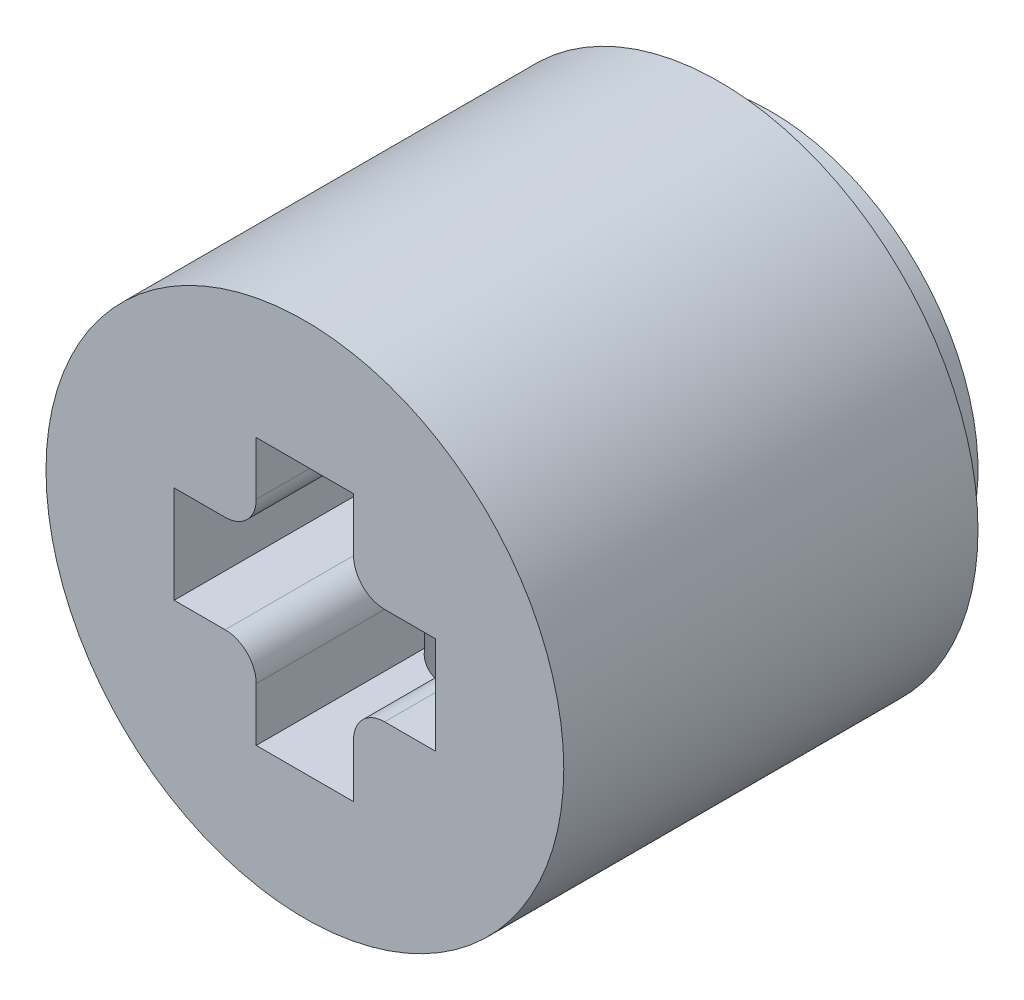
SolidWorks part; units mm, degrees
ref_plane "正面" through (0, 0, 0) normal (0, 0, 1) x (1, 0, 0)
ref_plane "平面" through (0, 0, 0) normal (0, 1, 0) x (1, 0, 0)
ref_plane "右側面" through (0, 0, 0) normal (1, 0, 0) x (0, 0, -1)
sketch "ｽｹｯﾁ1" plane through (0, 0, 0) normal (0, 0, 1) x (1, 0, 0)
  circle A0 centre (0, 0) radius 5
  dimension "D1" = 10
extrude "ﾎﾞｽ - 押し出し1" add sketch "ｽｹｯﾁ1" along normal blind 8
sketch "ｽｹｯﾁ4" plane through (0, 0, 0) normal (0, 0, -1) x (-1, 0, 0)
  circle A0 centre (0, 0) radius 4
  dimension "D1" = 8
extrude "ﾎﾞｽ - 押し出し2" add sketch "ｽｹｯﾁ4" along normal blind 1
sketch "ｽｹｯﾁ2" plane through (0, 0, 8) normal (0, 0, 1) x (1, 0, 0)
  line L1 (-2.525, 0.94) -> (2.525, 0.94)
  line L2 (-2.525, 0.94) -> (-2.525, -0.94)
  line L3 (-2.525, -0.94) -> (2.525, -0.94)
  line L4 (2.525, 0.94) -> (2.525, -0.94)
  line L5 (-2.525, 0.94) -> (2.525, -0.94) construction
  line L6 (-2.525, -0.94) -> (2.525, 0.94) construction
  line L7 (-0.94, 2.575) -> (0.94, 2.575)
  line L8 (-0.94, 2.575) -> (-0.94, -2.575)
  line L9 (-0.94, -2.575) -> (0.94, -2.575)
  line L10 (0.94, 2.575) -> (0.94, -2.575)
  line L11 (-0.94, 2.575) -> (0.94, -2.575) construction
  line L12 (-0.94, -2.575) -> (0.94, 2.575) construction
  point P0 (0, 0)
  point P6 (0, 0)
  dimension "D1" = 5.15
  dimension "D2" = 5.05
  dimension "D3" = 1.88
  dimension "D4" = 1.88
extrude "ｶｯﾄ - 押し出し1" cut sketch "ｽｹｯﾁ2" against normal through all contours L1 L4 L3 L2 | L10 L9 L8 L7
fillet "ﾌｨﾚｯﾄ1" radius 0.6 4 edges at (-0.94, 0.94, 3.5) (-0.94, -0.94, 3.5) (0.94, -0.94, 3.5) (0.94, 0.94, 3.5)
sketch "ｽｹｯﾁ3" plane through (0, -2.575, 0) normal (0, 1, 0) x (1, 0, 0)
  line L0 (0, 0) -> (0, -8) construction
  line L1 (-5, -8) -> (5, -8) construction
  line L2 (0, -4) -> (5.4928, -4) construction
  circle A0 centre (0, -4) radius 1.2
  dimension "D1" = 2.4
extrude "ｶｯﾄ - 押し出し2" cut sketch "ｽｹｯﾁ3" against normal through all and the other way blind 0.5
